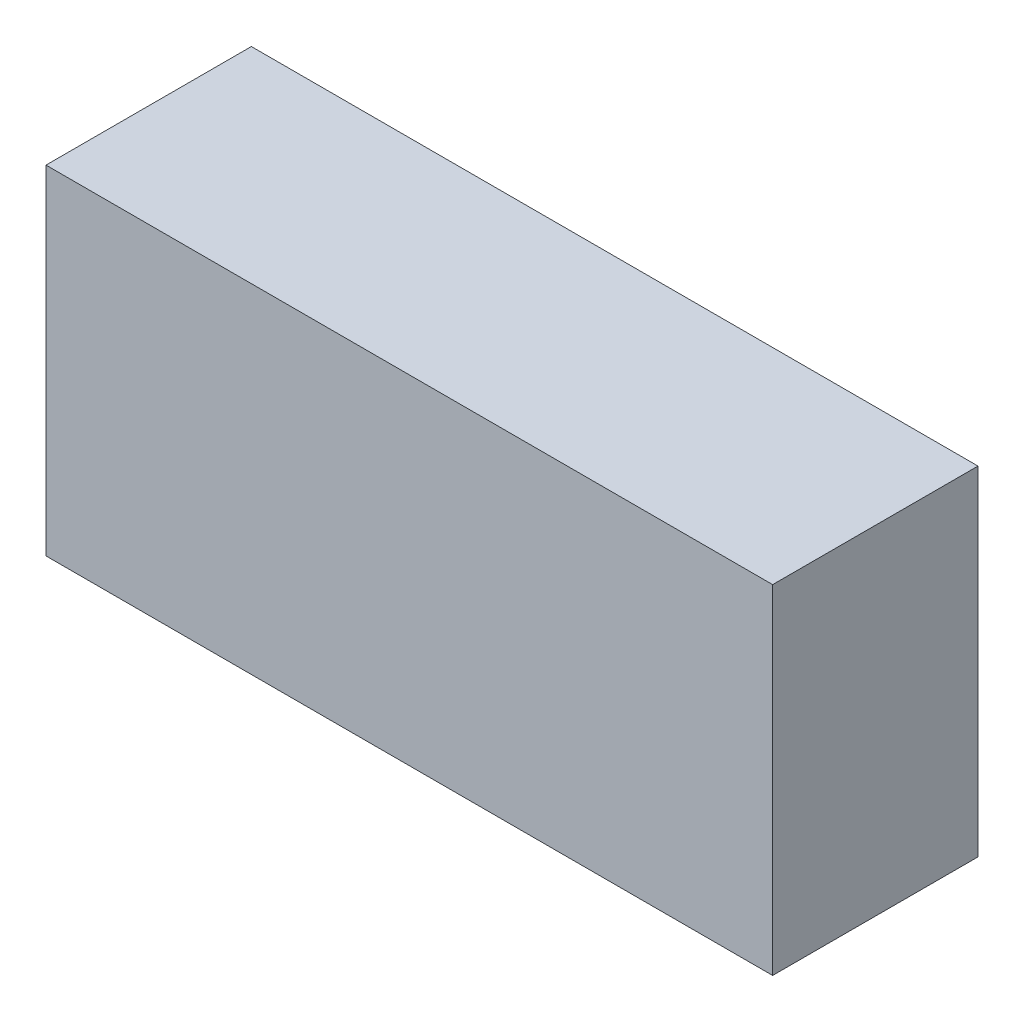
SolidWorks part; units mm, degrees
ref_plane "Front" through (0, 0, 0) normal (0, 0, 1) x (1, 0, 0)
ref_plane "Top" through (0, 0, 0) normal (0, 1, 0) x (1, 0, 0)
ref_plane "Right" through (0, 0, 0) normal (1, 0, 0) x (0, 0, -1)
sketch "Sketch1" plane through (0, 0, 0) normal (0, 1, 0) x (1, 0, 0)
  line L1 (-16.1, -4.55) -> (16.1, -4.55)
  line L2 (-16.1, -4.55) -> (-16.1, 4.55)
  line L3 (-16.1, 4.55) -> (16.1, 4.55)
  line L4 (16.1, -4.55) -> (16.1, 4.55)
  line L5 (-16.1, -4.55) -> (16.1, 4.55) construction
  line L6 (-16.1, 4.55) -> (16.1, -4.55) construction
  point P0 (0, 0)
  dimension "D1" = 32.2
  dimension "D2" = 9.1
extrude "Boss-Extrude1" add sketch "Sketch1" along normal blind 15
